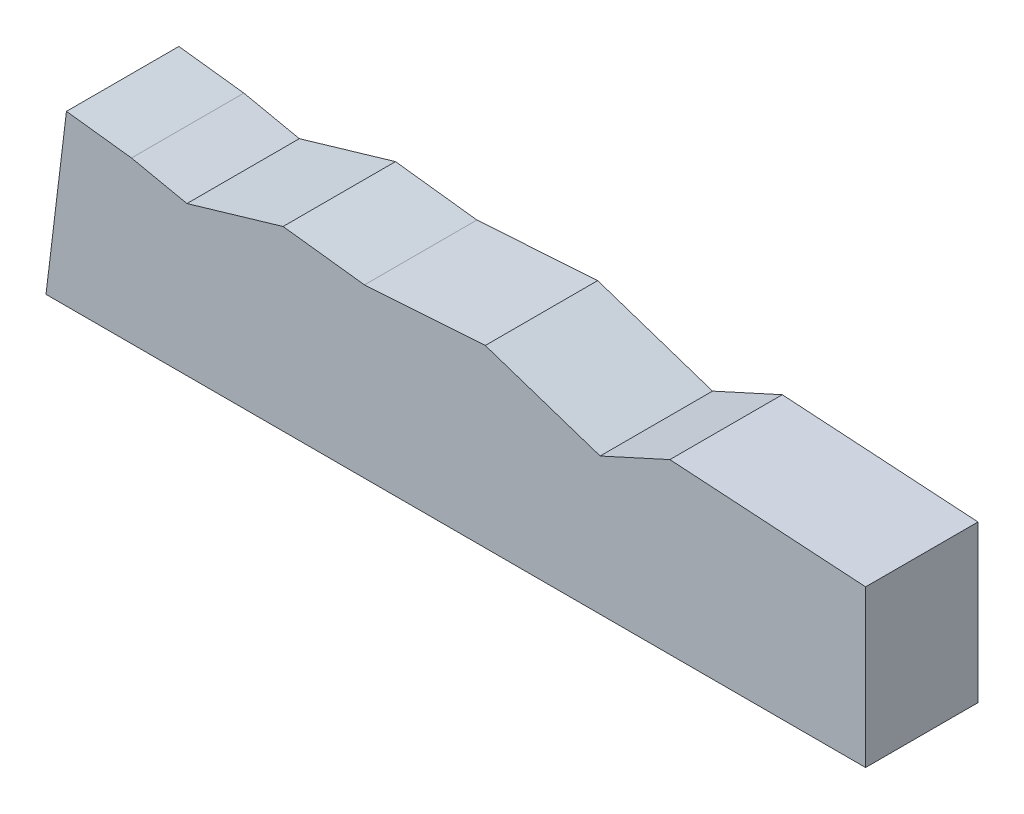
SolidWorks part; units mm, degrees
ref_plane "Front Plane" through (0, 0, 0) normal (0, 0, 1) x (1, 0, 0)
ref_plane "Top Plane" through (0, 0, 0) normal (0, 1, 0) x (1, 0, 0)
ref_plane "Right Plane" through (0, 0, 0) normal (1, 0, 0) x (0, 0, -1)
sketch "Sketch1" plane through (0, 0, 0) normal (0, 0, 1) x (1, 0, 0)
  line L11 (174.2221, -57.2381) -> (87.1568, -51.7423)
  line L12 (87.1568, -51.7423) -> (56.1353, -65.8709)
  line L13 (56.1353, -65.8709) -> (5.0423, -48.84)
  line L14 (5.0423, -48.84) -> (-48.6934, -52.3636)
  line L15 (-48.6934, -52.3636) -> (-84.9091, -47.9738)
  line L16 (-84.9091, -47.9738) -> (-127.6764, -60.5189)
  line L17 (-127.6764, -60.5189) -> (-152.3475, -55.3)
  line L18 (-152.3475, -55.3) -> (-181.2773, -51.7933)
  line L19 (-181.2773, -51.7933) -> (-190.3759, -126.8568)
  line L20 (-190.3759, -126.8568) -> (174.2221, -126.8568)
  line L21 (174.2221, -126.8568) -> (174.2221, -57.2381)
  line L22 (174.2221, -57.2381) -> (87.1568, -51.7423)
  line L23 (87.1568, -51.7423) -> (56.1353, -65.8709)
  line L24 (56.1353, -65.8709) -> (5.0423, -48.84)
  line L25 (5.0423, -48.84) -> (-48.6934, -52.3636)
  line L26 (-48.6934, -52.3636) -> (-84.9091, -47.9738)
  line L27 (-84.9091, -47.9738) -> (-127.6764, -60.5189)
  line L28 (-127.6764, -60.5189) -> (-152.3475, -55.3)
  line L29 (-152.3475, -55.3) -> (-181.2773, -51.7933)
  line L30 (-181.2773, -51.7933) -> (-190.3759, -126.8568)
  line L31 (-190.3759, -126.8568) -> (174.2221, -126.8568)
  line L32 (174.2221, -126.8568) -> (174.2221, -57.2381)
  dimension "D1" = 0
extrude "Boss-Extrude1" add sketch "Sketch1" along normal mid plane 50
